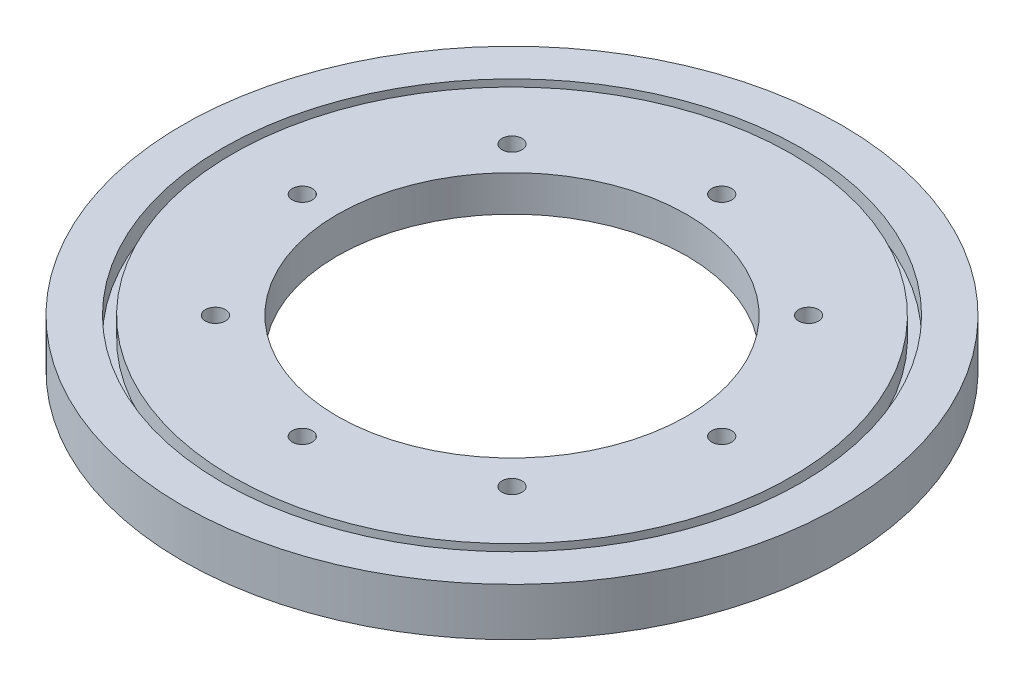
SolidWorks part; units mm, degrees
ref_plane "Front Plane" through (0, 0, 0) normal (0, 0, 1) x (1, 0, 0)
ref_plane "Top Plane" through (0, 0, 0) normal (0, 1, 0) x (1, 0, 0)
ref_plane "Right Plane" through (0, 0, 0) normal (1, 0, 0) x (0, 0, -1)
sketch "Sketch1" plane through (0, 0, 0) normal (0, 1, 0) x (1, 0, 0)
  circle A0 centre (0, 0) radius 165
  point P0 (0, 0)
  dimension "D1" = 330
extrude "plate" add sketch "Sketch1" along normal blind 24
sketch "Sketch2" plane through (0, 24, 0) normal (0, 1, 0) x (1, 0, 0)
  circle A0 centre (0, 0) radius 87.5
  dimension "D1" = 175
extrude "bearing-hole" cut sketch "Sketch2" against normal through all
sketch "Sketch4" plane through (0, 24, 0) normal (0, 1, 0) x (1, 0, 0)
  circle A0 centre (0, 0) radius 145
  circle A1 centre (0, 0) radius 140
  point P0 (0, 0)
  point P6 (0, 0)
  dimension "D1" = 290
  dimension "D2" = 280
extrude "Cut-Extrude3" cut sketch "Sketch4" against normal blind 10
sketch "Sketch5" plane through (0, 0, 0) normal (0, -1, 0) x (1, 0, 0)
  circle A0 centre (0, 0) radius 125
  dimension "D1" = 250
extrude "Cut-Extrude4" cut sketch "Sketch5" against normal blind 6
sketch "Sketch6" plane through (0, 6, 0) normal (0, -1, 0) x (1, 0, 0)
  circle A0 centre (0, 105) radius 5
  circle A1 centre (74.2462, 74.2462) radius 5
  circle A2 centre (105, 0) radius 5
  circle A3 centre (74.2462, -74.2462) radius 5
  circle A4 centre (0, -105) radius 5
  circle A5 centre (-74.2462, -74.2462) radius 5
  circle A6 centre (-105, 0) radius 5
  circle A7 centre (-74.2462, 74.2462) radius 5
  point P19 (0, 0)
  dimension "D1" = 10
  dimension "D2" = 105
  dimension "D3" = 8
extrude "Cut-Extrude5" cut sketch "Sketch6" against normal through all
